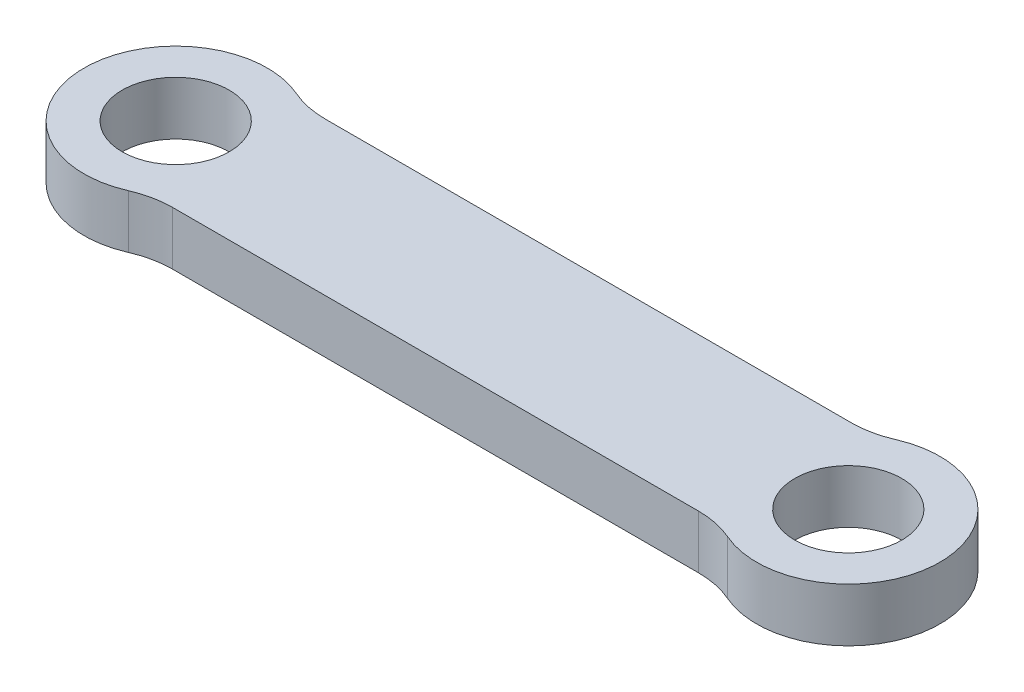
SolidWorks part; units mm, degrees
ref_plane "Front Plane" through (0, 0, 0) normal (0, 0, 1) x (1, 0, 0)
ref_plane "Top Plane" through (0, 0, 0) normal (0, 1, 0) x (1, 0, 0)
ref_plane "Right Plane" through (0, 0, 0) normal (1, 0, 0) x (0, 0, -1)
sketch "Sketch1" plane through (0, 0, 0) normal (0, 1, 0) x (1, 0, 0)
  line L0 (0, 0) -> (22, 0) construction
  line L1 (1.6583, 2.5) -> (20.3417, 2.5)
  line L2 (1.6583, -2.5) -> (20.3417, -2.5)
  circle A0 centre (0, 0) radius 3
  circle A1 centre (22, 0) radius 3
  circle A2 centre (0, 0) radius 1.75
  circle A3 centre (22, 0) radius 1.75
  dimension "D1" = 6
  dimension "D3" = 6
  dimension "D5" = 3.5
  dimension "D6" = 3.5
  dimension "D2" = 22
  dimension "D4" = 2.5
extrude "Boss-Extrude1" add sketch "Sketch1" along normal blind 1.75
fillet "Fillet1" radius 3 4 edges at (1.6583, 0.875, 2.5) (20.3417, 0.875, 2.5) (20.3417, 0.875, -2.5) (1.6583, 0.875, -2.5)
